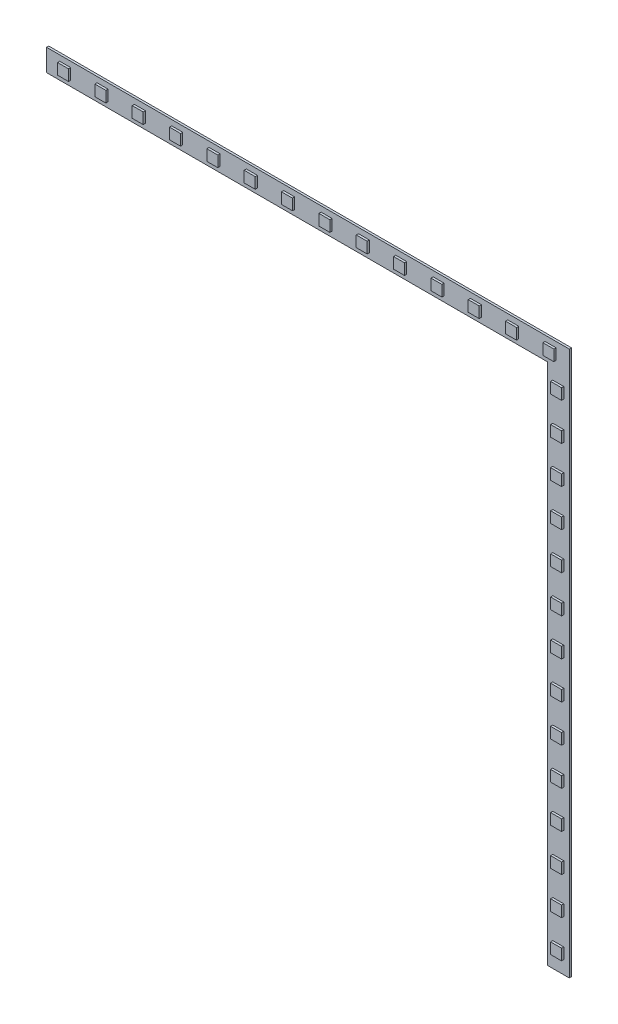
SolidWorks part; units mm, degrees
ref_plane "前基準面" through (0, 0, 0) normal (0, 0, 1) x (1, 0, 0)
ref_plane "上基準面" through (0, 0, 0) normal (0, 1, 0) x (1, 0, 0)
ref_plane "右基準面" through (0, 0, 0) normal (1, 0, 0) x (0, 0, -1)
sketch "草圖1" plane through (0, 0, 0) normal (0, 0, 1) x (1, 0, 0)
  line L1 (0, 0) -> (238, 0)
  line L2 (0, 0) -> (0, -10)
  line L3 (0, -10) -> (228, -10)
  line L4 (238, 0) -> (238, -10)
  line L6 (238, -10) -> (238, -248)
  line L7 (238, -248) -> (228, -248)
  line L8 (228, -10) -> (228, -248)
  dimension "D1" = 10
  dimension "D2" = 238
  dimension "D3" = 10
  dimension "D4" = 238
extrude "填料-伸長1" add sketch "草圖1" along normal blind 1
sketch "草圖2" plane through (0, 0, 1) normal (0, 0, 1) x (1, 0, 0)
  line L0 (17, 0) -> (17, -10) construction
  line L1 (238, 0) -> (0, 0) construction
  line L2 (0, -10) -> (228, -10) construction
  line L3 (0, 0) -> (0, -10) construction
  line L4 (17, -5) -> (0, -5) construction
  line L5 (28, -2.5) -> (28, -7.5)
  line L6 (11, -2.5) -> (6, -2.5)
  line L7 (11, -2.5) -> (11, -7.5)
  line L8 (11, -7.5) -> (6, -7.5)
  line L9 (6, -2.5) -> (6, -7.5)
  line L10 (11, -2.5) -> (6, -7.5) construction
  line L11 (11, -7.5) -> (6, -2.5) construction
  line L12 (28, -2.5) -> (23, -2.5)
  line L13 (23, -2.5) -> (23, -7.5)
  line L14 (28, -7.5) -> (23, -7.5)
  line L15 (45, -2.5) -> (45, -7.5)
  line L16 (45, -2.5) -> (40, -2.5)
  line L17 (40, -2.5) -> (40, -7.5)
  line L18 (45, -7.5) -> (40, -7.5)
  line L19 (62, -2.5) -> (62, -7.5)
  line L20 (62, -2.5) -> (57, -2.5)
  line L21 (57, -2.5) -> (57, -7.5)
  line L22 (62, -7.5) -> (57, -7.5)
  line L23 (79, -2.5) -> (79, -7.5)
  line L24 (79, -2.5) -> (74, -2.5)
  line L25 (74, -2.5) -> (74, -7.5)
  line L26 (79, -7.5) -> (74, -7.5)
  line L27 (96, -2.5) -> (96, -7.5)
  line L28 (96, -2.5) -> (91, -2.5)
  line L29 (91, -2.5) -> (91, -7.5)
  line L30 (96, -7.5) -> (91, -7.5)
  line L31 (113, -2.5) -> (113, -7.5)
  line L32 (113, -2.5) -> (108, -2.5)
  line L33 (108, -2.5) -> (108, -7.5)
  line L34 (113, -7.5) -> (108, -7.5)
  line L35 (130, -2.5) -> (130, -7.5)
  line L36 (130, -2.5) -> (125, -2.5)
  line L37 (125, -2.5) -> (125, -7.5)
  line L38 (130, -7.5) -> (125, -7.5)
  line L39 (147, -2.5) -> (147, -7.5)
  line L40 (147, -2.5) -> (142, -2.5)
  line L41 (142, -2.5) -> (142, -7.5)
  line L42 (147, -7.5) -> (142, -7.5)
  line L43 (164, -2.5) -> (164, -7.5)
  line L44 (164, -2.5) -> (159, -2.5)
  line L45 (159, -2.5) -> (159, -7.5)
  line L46 (164, -7.5) -> (159, -7.5)
  line L47 (181, -2.5) -> (181, -7.5)
  line L48 (181, -2.5) -> (176, -2.5)
  line L49 (176, -2.5) -> (176, -7.5)
  line L50 (181, -7.5) -> (176, -7.5)
  line L51 (198, -2.5) -> (198, -7.5)
  line L52 (198, -2.5) -> (193, -2.5)
  line L53 (193, -2.5) -> (193, -7.5)
  line L54 (198, -7.5) -> (193, -7.5)
  line L55 (215, -2.5) -> (215, -7.5)
  line L56 (215, -2.5) -> (210, -2.5)
  line L57 (210, -2.5) -> (210, -7.5)
  line L58 (215, -7.5) -> (210, -7.5)
  line L59 (232, -2.5) -> (232, -7.5)
  line L60 (232, -2.5) -> (227, -2.5)
  line L61 (227, -2.5) -> (227, -7.5)
  line L62 (232, -7.5) -> (227, -7.5)
  line L63 (238, -231) -> (228, -231) construction
  line L64 (238, -248) -> (238, 0) construction
  line L65 (228, -10) -> (228, -248) construction
  line L66 (228, -248) -> (238, -248) construction
  line L67 (233, -231) -> (233, -248) construction
  line L68 (235.5, -220) -> (235.5, -225)
  line L69 (235.5, -237) -> (230.5, -237)
  line L70 (235.5, -237) -> (235.5, -242)
  line L71 (235.5, -242) -> (230.5, -242)
  line L72 (230.5, -237) -> (230.5, -242)
  line L73 (235.5, -237) -> (230.5, -242) construction
  line L74 (235.5, -242) -> (230.5, -237) construction
  line L75 (235.5, -220) -> (230.5, -220)
  line L76 (230.5, -220) -> (230.5, -225)
  line L77 (235.5, -225) -> (230.5, -225)
  line L78 (235.5, -203) -> (235.5, -208)
  line L79 (235.5, -203) -> (230.5, -203)
  line L80 (230.5, -203) -> (230.5, -208)
  line L81 (235.5, -208) -> (230.5, -208)
  line L82 (235.5, -186) -> (235.5, -191)
  line L83 (235.5, -186) -> (230.5, -186)
  line L84 (230.5, -186) -> (230.5, -191)
  line L85 (235.5, -191) -> (230.5, -191)
  line L86 (235.5, -169) -> (235.5, -174)
  line L87 (235.5, -169) -> (230.5, -169)
  line L88 (230.5, -169) -> (230.5, -174)
  line L89 (235.5, -174) -> (230.5, -174)
  line L90 (235.5, -152) -> (235.5, -157)
  line L91 (235.5, -152) -> (230.5, -152)
  line L92 (230.5, -152) -> (230.5, -157)
  line L93 (235.5, -157) -> (230.5, -157)
  line L94 (235.5, -135) -> (235.5, -140)
  line L95 (235.5, -135) -> (230.5, -135)
  line L96 (230.5, -135) -> (230.5, -140)
  line L97 (235.5, -140) -> (230.5, -140)
  line L98 (235.5, -118) -> (235.5, -123)
  line L99 (235.5, -118) -> (230.5, -118)
  line L100 (230.5, -118) -> (230.5, -123)
  line L101 (235.5, -123) -> (230.5, -123)
  line L102 (235.5, -101) -> (235.5, -106)
  line L103 (235.5, -101) -> (230.5, -101)
  line L104 (230.5, -101) -> (230.5, -106)
  line L105 (235.5, -106) -> (230.5, -106)
  line L106 (235.5, -84) -> (235.5, -89)
  line L107 (235.5, -84) -> (230.5, -84)
  line L108 (230.5, -84) -> (230.5, -89)
  line L109 (235.5, -89) -> (230.5, -89)
  line L110 (235.5, -67) -> (235.5, -72)
  line L111 (235.5, -67) -> (230.5, -67)
  line L112 (230.5, -67) -> (230.5, -72)
  line L113 (235.5, -72) -> (230.5, -72)
  line L114 (235.5, -50) -> (235.5, -55)
  line L115 (235.5, -50) -> (230.5, -50)
  line L116 (230.5, -50) -> (230.5, -55)
  line L117 (235.5, -55) -> (230.5, -55)
  line L118 (235.5, -33) -> (235.5, -38)
  line L119 (235.5, -33) -> (230.5, -33)
  line L120 (230.5, -33) -> (230.5, -38)
  line L121 (235.5, -38) -> (230.5, -38)
  line L122 (235.5, -16) -> (235.5, -21)
  line L123 (235.5, -16) -> (230.5, -16)
  line L124 (230.5, -16) -> (230.5, -21)
  line L125 (235.5, -21) -> (230.5, -21)
  point P10 (8.5, -5)
  point P77 (233, -239.5)
  dimension "D1" = 17
  dimension "D2" = 5
  dimension "D3" = 5
  dimension "D5" = 17
  dimension "D6" = 5
  dimension "D7" = 5
  dimension "D4" = 14
  dimension "D8" = 14
extrude "填料-伸長2" add sketch "草圖2" along normal blind 1
sketch "草圖3" plane through (0, 0, 1) normal (0, 0, 1) x (1, 0, 0)
  line L0 (17, 0) -> (17, -10) construction
  line L1 (238, 0) -> (0, 0) construction
  line L2 (0, -10) -> (228, -10) construction
  line L3 (0, 0) -> (0, -10) construction
  line L4 (-2, -2) -> (2, -2) construction
  line L5 (-2, -1) -> (2, -1)
  line L6 (-2, -3) -> (2, -3)
  line L7 (17, -5) -> (0, -5) construction
  line L8 (-2, -8) -> (2, -8) construction
  line L9 (-2, -9) -> (2, -9)
  line L10 (-2, -7) -> (2, -7)
  line L11 (-2, -5) -> (2, -5) construction
  line L12 (-2, -4) -> (2, -4)
  line L13 (-2, -6) -> (2, -6)
  line L14 (8.5, -5) -> (8.5, -1.429) construction
  line L15 (19, -8) -> (15, -8) construction
  line L16 (19, -9) -> (15, -9)
  line L17 (19, -7) -> (15, -7)
  line L18 (19, -5) -> (15, -5) construction
  line L19 (19, -4) -> (15, -4)
  line L20 (19, -6) -> (15, -6)
  line L21 (19, -2) -> (15, -2) construction
  line L22 (19, -1) -> (15, -1)
  line L23 (19, -3) -> (15, -3)
  line L24 (36, -1) -> (32, -1)
  line L25 (36, -3) -> (32, -3)
  line L26 (36, -4) -> (32, -4)
  line L27 (36, -6) -> (32, -6)
  line L28 (36, -9) -> (32, -9)
  line L29 (36, -7) -> (32, -7)
  line L30 (15, -3) -> (19, -3)
  line L31 (15, -1) -> (19, -1)
  line L32 (15, -4) -> (19, -4)
  line L33 (15, -6) -> (19, -6)
  line L34 (15, -9) -> (19, -9)
  line L35 (15, -7) -> (19, -7)
  line L36 (15, -2) -> (19, -2) construction
  line L37 (15, -8) -> (19, -8) construction
  line L38 (15, -5) -> (19, -5) construction
  line L39 (36, -8) -> (32, -8) construction
  line L40 (36, -5) -> (32, -5) construction
  line L41 (36, -2) -> (32, -2) construction
  line L42 (53, -1) -> (49, -1)
  line L43 (53, -3) -> (49, -3)
  line L44 (53, -4) -> (49, -4)
  line L45 (53, -6) -> (49, -6)
  line L46 (53, -9) -> (49, -9)
  line L47 (53, -7) -> (49, -7)
  line L48 (32, -3) -> (36, -3)
  line L49 (32, -1) -> (36, -1)
  line L50 (32, -4) -> (36, -4)
  line L51 (32, -6) -> (36, -6)
  line L52 (32, -9) -> (36, -9)
  line L53 (32, -7) -> (36, -7)
  line L54 (32, -2) -> (36, -2) construction
  line L55 (32, -8) -> (36, -8) construction
  line L56 (32, -5) -> (36, -5) construction
  line L57 (53, -8) -> (49, -8) construction
  line L58 (53, -5) -> (49, -5) construction
  line L59 (53, -2) -> (49, -2) construction
  line L60 (70, -1) -> (66, -1)
  line L61 (70, -3) -> (66, -3)
  line L62 (70, -4) -> (66, -4)
  line L63 (70, -6) -> (66, -6)
  line L64 (70, -9) -> (66, -9)
  line L65 (70, -7) -> (66, -7)
  line L66 (49, -3) -> (53, -3)
  line L67 (49, -1) -> (53, -1)
  line L68 (49, -4) -> (53, -4)
  line L69 (49, -6) -> (53, -6)
  line L70 (49, -9) -> (53, -9)
  line L71 (49, -7) -> (53, -7)
  line L72 (49, -2) -> (53, -2) construction
  line L73 (49, -8) -> (53, -8) construction
  line L74 (49, -5) -> (53, -5) construction
  line L75 (70, -8) -> (66, -8) construction
  line L76 (70, -5) -> (66, -5) construction
  line L77 (70, -2) -> (66, -2) construction
  line L78 (87, -1) -> (83, -1)
  line L79 (87, -3) -> (83, -3)
  line L80 (87, -4) -> (83, -4)
  line L81 (87, -6) -> (83, -6)
  line L82 (87, -9) -> (83, -9)
  line L83 (87, -7) -> (83, -7)
  line L84 (66, -3) -> (70, -3)
  line L85 (66, -1) -> (70, -1)
  line L86 (66, -4) -> (70, -4)
  line L87 (66, -6) -> (70, -6)
  line L88 (66, -9) -> (70, -9)
  line L89 (66, -7) -> (70, -7)
  line L90 (66, -2) -> (70, -2) construction
  line L91 (66, -8) -> (70, -8) construction
  line L92 (66, -5) -> (70, -5) construction
  line L93 (87, -8) -> (83, -8) construction
  line L94 (87, -5) -> (83, -5) construction
  line L95 (87, -2) -> (83, -2) construction
  line L96 (104, -1) -> (100, -1)
  line L97 (104, -3) -> (100, -3)
  line L98 (104, -4) -> (100, -4)
  line L99 (104, -6) -> (100, -6)
  line L100 (104, -9) -> (100, -9)
  line L101 (104, -7) -> (100, -7)
  line L102 (83, -3) -> (87, -3)
  line L103 (83, -1) -> (87, -1)
  line L104 (83, -4) -> (87, -4)
  line L105 (83, -6) -> (87, -6)
  line L106 (83, -9) -> (87, -9)
  line L107 (83, -7) -> (87, -7)
  line L108 (83, -2) -> (87, -2) construction
  line L109 (83, -8) -> (87, -8) construction
  line L110 (83, -5) -> (87, -5) construction
  line L111 (104, -8) -> (100, -8) construction
  line L112 (104, -5) -> (100, -5) construction
  line L113 (104, -2) -> (100, -2) construction
  line L114 (121, -1) -> (117, -1)
  line L115 (121, -3) -> (117, -3)
  line L116 (121, -4) -> (117, -4)
  line L117 (121, -6) -> (117, -6)
  line L118 (121, -9) -> (117, -9)
  line L119 (121, -7) -> (117, -7)
  line L120 (100, -3) -> (104, -3)
  line L121 (100, -1) -> (104, -1)
  line L122 (100, -4) -> (104, -4)
  line L123 (100, -6) -> (104, -6)
  line L124 (100, -9) -> (104, -9)
  line L125 (100, -7) -> (104, -7)
  line L126 (100, -2) -> (104, -2) construction
  line L127 (100, -8) -> (104, -8) construction
  line L128 (100, -5) -> (104, -5) construction
  line L129 (121, -8) -> (117, -8) construction
  line L130 (121, -5) -> (117, -5) construction
  line L131 (121, -2) -> (117, -2) construction
  line L132 (138, -1) -> (134, -1)
  line L133 (138, -3) -> (134, -3)
  line L134 (138, -4) -> (134, -4)
  line L135 (138, -6) -> (134, -6)
  line L136 (138, -9) -> (134, -9)
  line L137 (138, -7) -> (134, -7)
  line L138 (117, -3) -> (121, -3)
  line L139 (117, -1) -> (121, -1)
  line L140 (117, -4) -> (121, -4)
  line L141 (117, -6) -> (121, -6)
  line L142 (117, -9) -> (121, -9)
  line L143 (117, -7) -> (121, -7)
  line L144 (117, -2) -> (121, -2) construction
  line L145 (117, -8) -> (121, -8) construction
  line L146 (117, -5) -> (121, -5) construction
  line L147 (138, -8) -> (134, -8) construction
  line L148 (138, -5) -> (134, -5) construction
  line L149 (138, -2) -> (134, -2) construction
  line L150 (155, -1) -> (151, -1)
  line L151 (155, -3) -> (151, -3)
  line L152 (155, -4) -> (151, -4)
  line L153 (155, -6) -> (151, -6)
  line L154 (155, -9) -> (151, -9)
  line L155 (155, -7) -> (151, -7)
  line L156 (134, -3) -> (138, -3)
  line L157 (134, -1) -> (138, -1)
  line L158 (134, -4) -> (138, -4)
  line L159 (134, -6) -> (138, -6)
  line L160 (134, -9) -> (138, -9)
  line L161 (134, -7) -> (138, -7)
  line L162 (134, -2) -> (138, -2) construction
  line L163 (134, -8) -> (138, -8) construction
  line L164 (134, -5) -> (138, -5) construction
  line L165 (155, -8) -> (151, -8) construction
  line L166 (155, -5) -> (151, -5) construction
  line L167 (155, -2) -> (151, -2) construction
  line L168 (172, -1) -> (168, -1)
  line L169 (172, -3) -> (168, -3)
  line L170 (172, -4) -> (168, -4)
  line L171 (172, -6) -> (168, -6)
  line L172 (172, -9) -> (168, -9)
  line L173 (172, -7) -> (168, -7)
  line L174 (151, -3) -> (155, -3)
  line L175 (151, -1) -> (155, -1)
  line L176 (151, -4) -> (155, -4)
  line L177 (151, -6) -> (155, -6)
  line L178 (151, -9) -> (155, -9)
  line L179 (151, -7) -> (155, -7)
  line L180 (151, -2) -> (155, -2) construction
  line L181 (151, -8) -> (155, -8) construction
  line L182 (151, -5) -> (155, -5) construction
  line L183 (172, -8) -> (168, -8) construction
  line L184 (172, -5) -> (168, -5) construction
  line L185 (172, -2) -> (168, -2) construction
  line L186 (189, -1) -> (185, -1)
  line L187 (189, -3) -> (185, -3)
  line L188 (189, -4) -> (185, -4)
  line L189 (189, -6) -> (185, -6)
  line L190 (189, -9) -> (185, -9)
  line L191 (189, -7) -> (185, -7)
  line L192 (168, -3) -> (172, -3)
  line L193 (168, -1) -> (172, -1)
  line L194 (168, -4) -> (172, -4)
  line L195 (168, -6) -> (172, -6)
  line L196 (168, -9) -> (172, -9)
  line L197 (168, -7) -> (172, -7)
  line L198 (168, -2) -> (172, -2) construction
  line L199 (168, -8) -> (172, -8) construction
  line L200 (168, -5) -> (172, -5) construction
  line L201 (189, -8) -> (185, -8) construction
  line L202 (189, -5) -> (185, -5) construction
  line L203 (189, -2) -> (185, -2) construction
  line L204 (206, -1) -> (202, -1)
  line L205 (206, -3) -> (202, -3)
  line L206 (206, -4) -> (202, -4)
  line L207 (206, -6) -> (202, -6)
  line L208 (206, -9) -> (202, -9)
  line L209 (206, -7) -> (202, -7)
  line L210 (185, -3) -> (189, -3)
  line L211 (185, -1) -> (189, -1)
  line L212 (185, -4) -> (189, -4)
  line L213 (185, -6) -> (189, -6)
  line L214 (185, -9) -> (189, -9)
  line L215 (185, -7) -> (189, -7)
  line L216 (185, -2) -> (189, -2) construction
  line L217 (185, -8) -> (189, -8) construction
  line L218 (185, -5) -> (189, -5) construction
  line L219 (206, -8) -> (202, -8) construction
  line L220 (206, -5) -> (202, -5) construction
  line L221 (206, -2) -> (202, -2) construction
  line L222 (223, -1) -> (219, -1)
  line L223 (223, -3) -> (219, -3)
  line L224 (223, -4) -> (219, -4)
  line L225 (223, -6) -> (219, -6)
  line L226 (223, -9) -> (219, -9)
  line L227 (223, -7) -> (219, -7)
  line L228 (202, -3) -> (206, -3)
  line L229 (202, -1) -> (206, -1)
  line L230 (202, -4) -> (206, -4)
  line L231 (202, -6) -> (206, -6)
  line L232 (202, -9) -> (206, -9)
  line L233 (202, -7) -> (206, -7)
  line L234 (202, -2) -> (206, -2) construction
  line L235 (202, -8) -> (206, -8) construction
  line L236 (202, -5) -> (206, -5) construction
  line L237 (223, -8) -> (219, -8) construction
  line L238 (223, -5) -> (219, -5) construction
  line L239 (223, -2) -> (219, -2) construction
  line L240 (240, -1) -> (236, -1)
  line L241 (240, -3) -> (236, -3)
  line L242 (240, -4) -> (236, -4)
  line L243 (240, -6) -> (236, -6)
  line L244 (240, -9) -> (236, -9)
  line L245 (240, -7) -> (236, -7)
  line L246 (219, -3) -> (223, -3)
  line L247 (219, -1) -> (223, -1)
  line L248 (219, -4) -> (223, -4)
  line L249 (219, -6) -> (223, -6)
  line L250 (219, -9) -> (223, -9)
  line L251 (219, -7) -> (223, -7)
  line L252 (219, -2) -> (223, -2) construction
  line L253 (219, -8) -> (223, -8) construction
  line L254 (219, -5) -> (223, -5) construction
  line L255 (240, -8) -> (236, -8) construction
  line L256 (240, -5) -> (236, -5) construction
  line L257 (240, -2) -> (236, -2) construction
  line L258 (19, -1) -> (36, -1) construction
  line L259 (233, -248) -> (233, -233.0079) construction
  line L260 (228, -248) -> (238, -248) construction
  line L261 (229.7303, -248) -> (229.7303, -244.1813) construction
  line L262 (228.9072, -248) -> (228.9072, -244.1813)
  line L263 (230.5534, -248) -> (230.5534, -244.1813)
  arc A0 (-2, -1) -> (-2, -3) centre (-2, -2) ccw
  arc A1 (2, -3) -> (2, -1) centre (2, -2) ccw
  arc A2 (-2, -9) -> (-2, -7) centre (-2, -8) cw
  arc A3 (2, -7) -> (2, -9) centre (2, -8) cw
  arc A4 (-2, -4) -> (-2, -6) centre (-2, -5) ccw
  arc A5 (2, -6) -> (2, -4) centre (2, -5) ccw
  arc A6 (19, -9) -> (19, -7) centre (19, -8) ccw
  arc A7 (15, -7) -> (15, -9) centre (15, -8) ccw
  arc A8 (19, -4) -> (19, -6) centre (19, -5) cw
  arc A9 (15, -6) -> (15, -4) centre (15, -5) cw
  arc A10 (19, -1) -> (19, -3) centre (19, -2) cw
  arc A11 (15, -3) -> (15, -1) centre (15, -2) cw
  arc A12 (32, -3) -> (32, -1) centre (32, -2) cw
  arc A13 (36, -1) -> (36, -3) centre (36, -2) cw
  arc A14 (32, -6) -> (32, -4) centre (32, -5) cw
  arc A15 (36, -4) -> (36, -6) centre (36, -5) cw
  arc A16 (32, -7) -> (32, -9) centre (32, -8) ccw
  arc A17 (36, -9) -> (36, -7) centre (36, -8) ccw
  arc A18 (15, -1) -> (15, -3) centre (15, -2) ccw
  arc A19 (19, -3) -> (19, -1) centre (19, -2) ccw
  arc A20 (19, -6) -> (19, -4) centre (19, -5) ccw
  arc A21 (15, -4) -> (15, -6) centre (15, -5) ccw
  arc A22 (19, -7) -> (19, -9) centre (19, -8) cw
  arc A23 (15, -9) -> (15, -7) centre (15, -8) cw
  arc A24 (49, -3) -> (49, -1) centre (49, -2) cw
  arc A25 (53, -1) -> (53, -3) centre (53, -2) cw
  arc A26 (49, -6) -> (49, -4) centre (49, -5) cw
  arc A27 (53, -4) -> (53, -6) centre (53, -5) cw
  arc A28 (49, -7) -> (49, -9) centre (49, -8) ccw
  arc A29 (53, -9) -> (53, -7) centre (53, -8) ccw
  arc A30 (32, -1) -> (32, -3) centre (32, -2) ccw
  arc A31 (36, -3) -> (36, -1) centre (36, -2) ccw
  arc A32 (36, -6) -> (36, -4) centre (36, -5) ccw
  arc A33 (32, -4) -> (32, -6) centre (32, -5) ccw
  arc A34 (36, -7) -> (36, -9) centre (36, -8) cw
  arc A35 (32, -9) -> (32, -7) centre (32, -8) cw
  arc A36 (66, -3) -> (66, -1) centre (66, -2) cw
  arc A37 (70, -1) -> (70, -3) centre (70, -2) cw
  arc A38 (66, -6) -> (66, -4) centre (66, -5) cw
  arc A39 (70, -4) -> (70, -6) centre (70, -5) cw
  arc A40 (66, -7) -> (66, -9) centre (66, -8) ccw
  arc A41 (70, -9) -> (70, -7) centre (70, -8) ccw
  arc A42 (49, -1) -> (49, -3) centre (49, -2) ccw
  arc A43 (53, -3) -> (53, -1) centre (53, -2) ccw
  arc A44 (53, -6) -> (53, -4) centre (53, -5) ccw
  arc A45 (49, -4) -> (49, -6) centre (49, -5) ccw
  arc A46 (53, -7) -> (53, -9) centre (53, -8) cw
  arc A47 (49, -9) -> (49, -7) centre (49, -8) cw
  arc A48 (83, -3) -> (83, -1) centre (83, -2) cw
  arc A49 (87, -1) -> (87, -3) centre (87, -2) cw
  arc A50 (83, -6) -> (83, -4) centre (83, -5) cw
  arc A51 (87, -4) -> (87, -6) centre (87, -5) cw
  arc A52 (83, -7) -> (83, -9) centre (83, -8) ccw
  arc A53 (87, -9) -> (87, -7) centre (87, -8) ccw
  arc A54 (66, -1) -> (66, -3) centre (66, -2) ccw
  arc A55 (70, -3) -> (70, -1) centre (70, -2) ccw
  arc A56 (70, -6) -> (70, -4) centre (70, -5) ccw
  arc A57 (66, -4) -> (66, -6) centre (66, -5) ccw
  arc A58 (70, -7) -> (70, -9) centre (70, -8) cw
  arc A59 (66, -9) -> (66, -7) centre (66, -8) cw
  arc A60 (100, -3) -> (100, -1) centre (100, -2) cw
  arc A61 (104, -1) -> (104, -3) centre (104, -2) cw
  arc A62 (100, -6) -> (100, -4) centre (100, -5) cw
  arc A63 (104, -4) -> (104, -6) centre (104, -5) cw
  arc A64 (100, -7) -> (100, -9) centre (100, -8) ccw
  arc A65 (104, -9) -> (104, -7) centre (104, -8) ccw
  arc A66 (83, -1) -> (83, -3) centre (83, -2) ccw
  arc A67 (87, -3) -> (87, -1) centre (87, -2) ccw
  arc A68 (87, -6) -> (87, -4) centre (87, -5) ccw
  arc A69 (83, -4) -> (83, -6) centre (83, -5) ccw
  arc A70 (87, -7) -> (87, -9) centre (87, -8) cw
  arc A71 (83, -9) -> (83, -7) centre (83, -8) cw
  arc A72 (117, -3) -> (117, -1) centre (117, -2) cw
  arc A73 (121, -1) -> (121, -3) centre (121, -2) cw
  arc A74 (117, -6) -> (117, -4) centre (117, -5) cw
  arc A75 (121, -4) -> (121, -6) centre (121, -5) cw
  arc A76 (117, -7) -> (117, -9) centre (117, -8) ccw
  arc A77 (121, -9) -> (121, -7) centre (121, -8) ccw
  arc A78 (100, -1) -> (100, -3) centre (100, -2) ccw
  arc A79 (104, -3) -> (104, -1) centre (104, -2) ccw
  arc A80 (104, -6) -> (104, -4) centre (104, -5) ccw
  arc A81 (100, -4) -> (100, -6) centre (100, -5) ccw
  arc A82 (104, -7) -> (104, -9) centre (104, -8) cw
  arc A83 (100, -9) -> (100, -7) centre (100, -8) cw
  arc A84 (134, -3) -> (134, -1) centre (134, -2) cw
  arc A85 (138, -1) -> (138, -3) centre (138, -2) cw
  arc A86 (134, -6) -> (134, -4) centre (134, -5) cw
  arc A87 (138, -4) -> (138, -6) centre (138, -5) cw
  arc A88 (134, -7) -> (134, -9) centre (134, -8) ccw
  arc A89 (138, -9) -> (138, -7) centre (138, -8) ccw
  arc A90 (117, -1) -> (117, -3) centre (117, -2) ccw
  arc A91 (121, -3) -> (121, -1) centre (121, -2) ccw
  arc A92 (121, -6) -> (121, -4) centre (121, -5) ccw
  arc A93 (117, -4) -> (117, -6) centre (117, -5) ccw
  arc A94 (121, -7) -> (121, -9) centre (121, -8) cw
  arc A95 (117, -9) -> (117, -7) centre (117, -8) cw
  arc A96 (151, -3) -> (151, -1) centre (151, -2) cw
  arc A97 (155, -1) -> (155, -3) centre (155, -2) cw
  arc A98 (151, -6) -> (151, -4) centre (151, -5) cw
  arc A99 (155, -4) -> (155, -6) centre (155, -5) cw
  arc A100 (151, -7) -> (151, -9) centre (151, -8) ccw
  arc A101 (155, -9) -> (155, -7) centre (155, -8) ccw
  arc A102 (134, -1) -> (134, -3) centre (134, -2) ccw
  arc A103 (138, -3) -> (138, -1) centre (138, -2) ccw
  arc A104 (138, -6) -> (138, -4) centre (138, -5) ccw
  arc A105 (134, -4) -> (134, -6) centre (134, -5) ccw
  arc A106 (138, -7) -> (138, -9) centre (138, -8) cw
  arc A107 (134, -9) -> (134, -7) centre (134, -8) cw
  arc A108 (168, -3) -> (168, -1) centre (168, -2) cw
  arc A109 (172, -1) -> (172, -3) centre (172, -2) cw
  arc A110 (168, -6) -> (168, -4) centre (168, -5) cw
  arc A111 (172, -4) -> (172, -6) centre (172, -5) cw
  arc A112 (168, -7) -> (168, -9) centre (168, -8) ccw
  arc A113 (172, -9) -> (172, -7) centre (172, -8) ccw
  arc A114 (151, -1) -> (151, -3) centre (151, -2) ccw
  arc A115 (155, -3) -> (155, -1) centre (155, -2) ccw
  arc A116 (155, -6) -> (155, -4) centre (155, -5) ccw
  arc A117 (151, -4) -> (151, -6) centre (151, -5) ccw
  arc A118 (155, -7) -> (155, -9) centre (155, -8) cw
  arc A119 (151, -9) -> (151, -7) centre (151, -8) cw
  arc A120 (185, -3) -> (185, -1) centre (185, -2) cw
  arc A121 (189, -1) -> (189, -3) centre (189, -2) cw
  arc A122 (185, -6) -> (185, -4) centre (185, -5) cw
  arc A123 (189, -4) -> (189, -6) centre (189, -5) cw
  arc A124 (185, -7) -> (185, -9) centre (185, -8) ccw
  arc A125 (189, -9) -> (189, -7) centre (189, -8) ccw
  arc A126 (168, -1) -> (168, -3) centre (168, -2) ccw
  arc A127 (172, -3) -> (172, -1) centre (172, -2) ccw
  arc A128 (172, -6) -> (172, -4) centre (172, -5) ccw
  arc A129 (168, -4) -> (168, -6) centre (168, -5) ccw
  arc A130 (172, -7) -> (172, -9) centre (172, -8) cw
  arc A131 (168, -9) -> (168, -7) centre (168, -8) cw
  arc A132 (202, -3) -> (202, -1) centre (202, -2) cw
  arc A133 (206, -1) -> (206, -3) centre (206, -2) cw
  arc A134 (202, -6) -> (202, -4) centre (202, -5) cw
  arc A135 (206, -4) -> (206, -6) centre (206, -5) cw
  arc A136 (202, -7) -> (202, -9) centre (202, -8) ccw
  arc A137 (206, -9) -> (206, -7) centre (206, -8) ccw
  arc A138 (185, -1) -> (185, -3) centre (185, -2) ccw
  arc A139 (189, -3) -> (189, -1) centre (189, -2) ccw
  arc A140 (189, -6) -> (189, -4) centre (189, -5) ccw
  arc A141 (185, -4) -> (185, -6) centre (185, -5) ccw
  arc A142 (189, -7) -> (189, -9) centre (189, -8) cw
  arc A143 (185, -9) -> (185, -7) centre (185, -8) cw
  arc A144 (219, -3) -> (219, -1) centre (219, -2) cw
  arc A145 (223, -1) -> (223, -3) centre (223, -2) cw
  arc A146 (219, -6) -> (219, -4) centre (219, -5) cw
  arc A147 (223, -4) -> (223, -6) centre (223, -5) cw
  arc A148 (219, -7) -> (219, -9) centre (219, -8) ccw
  arc A149 (223, -9) -> (223, -7) centre (223, -8) ccw
  arc A150 (202, -1) -> (202, -3) centre (202, -2) ccw
  arc A151 (206, -3) -> (206, -1) centre (206, -2) ccw
  arc A152 (206, -6) -> (206, -4) centre (206, -5) ccw
  arc A153 (202, -4) -> (202, -6) centre (202, -5) ccw
  arc A154 (206, -7) -> (206, -9) centre (206, -8) cw
  arc A155 (202, -9) -> (202, -7) centre (202, -8) cw
  arc A156 (236, -3) -> (236, -1) centre (236, -2) cw
  arc A157 (240, -1) -> (240, -3) centre (240, -2) cw
  arc A158 (236, -6) -> (236, -4) centre (236, -5) cw
  arc A159 (240, -4) -> (240, -6) centre (240, -5) cw
  arc A160 (236, -7) -> (236, -9) centre (236, -8) ccw
  arc A161 (240, -9) -> (240, -7) centre (240, -8) ccw
  arc A162 (219, -1) -> (219, -3) centre (219, -2) ccw
  arc A163 (223, -3) -> (223, -1) centre (223, -2) ccw
  arc A164 (223, -6) -> (223, -4) centre (223, -5) ccw
  arc A165 (219, -4) -> (219, -6) centre (219, -5) ccw
  arc A166 (223, -7) -> (223, -9) centre (223, -8) cw
  arc A167 (219, -9) -> (219, -7) centre (219, -8) cw
  arc A168 (228.9072, -248) -> (230.5534, -248) centre (229.7303, -248) ccw
  arc A169 (230.5534, -244.1813) -> (228.9072, -244.1813) centre (229.7303, -244.1813) ccw
  point P10 (0, -2)
  point P17 (0, -8)
  point P26 (0, -5)
  point P35 (17, -8)
  point P42 (17, -5)
  point P49 (17, -2)
  point P58 (17, -2)
  point P65 (17, -8)
  point P72 (17, -5)
  point P79 (34, -8)
  point P86 (34, -5)
  point P93 (34, -2)
  point P100 (34, -2)
  point P107 (34, -8)
  point P114 (34, -5)
  point P121 (51, -8)
  point P128 (51, -5)
  point P135 (51, -2)
  point P142 (51, -2)
  point P149 (51, -8)
  point P156 (51, -5)
  point P163 (68, -8)
  point P170 (68, -5)
  point P177 (68, -2)
  point P184 (68, -2)
  point P191 (68, -8)
  point P198 (68, -5)
  point P205 (85, -8)
  point P212 (85, -5)
  point P219 (85, -2)
  point P226 (85, -2)
  point P233 (85, -8)
  point P240 (85, -5)
  point P247 (102, -8)
  point P254 (102, -5)
  point P261 (102, -2)
  point P268 (102, -2)
  point P275 (102, -8)
  point P282 (102, -5)
  point P289 (119, -8)
  point P296 (119, -5)
  point P303 (119, -2)
  point P310 (119, -2)
  point P317 (119, -8)
  point P324 (119, -5)
  point P331 (136, -8)
  point P338 (136, -5)
  point P345 (136, -2)
  point P352 (136, -2)
  point P359 (136, -8)
  point P366 (136, -5)
  point P373 (153, -8)
  point P380 (153, -5)
  point P387 (153, -2)
  point P394 (153, -2)
  point P401 (153, -8)
  point P408 (153, -5)
  point P415 (170, -8)
  point P422 (170, -5)
  point P429 (170, -2)
  point P436 (170, -2)
  point P443 (170, -8)
  point P450 (170, -5)
  point P457 (187, -8)
  point P464 (187, -5)
  point P471 (187, -2)
  point P478 (187, -2)
  point P485 (187, -8)
  point P492 (187, -5)
  point P499 (204, -8)
  point P506 (204, -5)
  point P513 (204, -2)
  point P520 (204, -2)
  point P527 (204, -8)
  point P534 (204, -5)
  point P541 (221, -8)
  point P548 (221, -5)
  point P555 (221, -2)
  point P562 (221, -2)
  point P569 (221, -8)
  point P576 (221, -5)
  point P583 (238, -8)
  point P590 (238, -5)
  point P597 (238, -2)
  point P608 (229.7303, -246.0907)
  point P613 (229.7303, -248)
  dimension "D1" = 17
  dimension "D2" = 4
  dimension "D3" = 2
  dimension "D4" = 1
  dimension "D5" = 2
  dimension "D6" = 4
  dimension "D8" = 17
  dimension "D7" = 14
